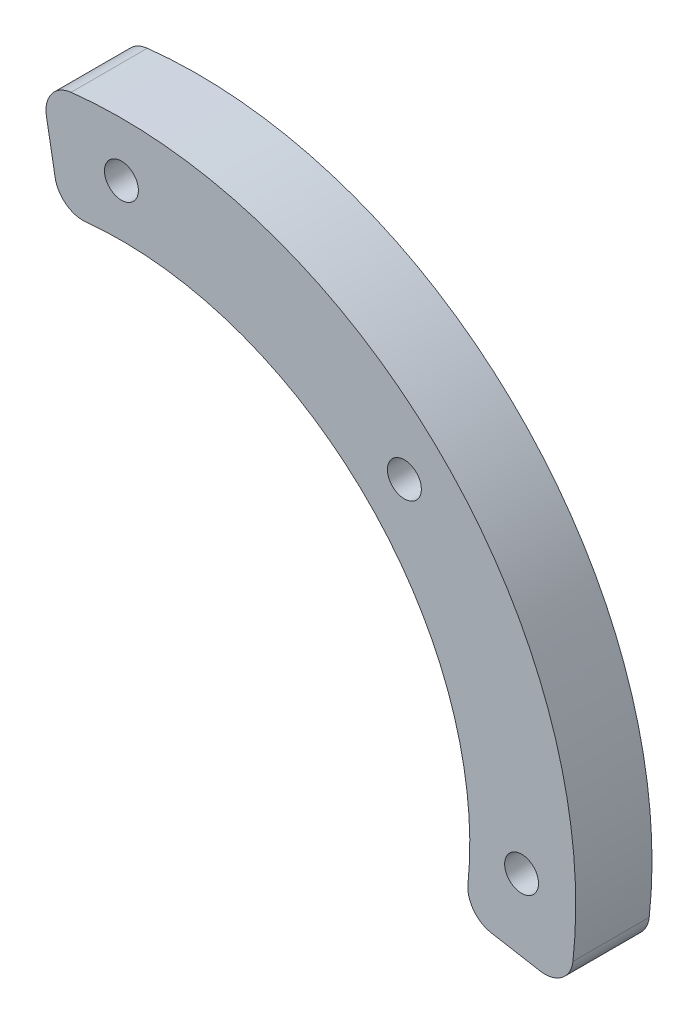
SolidWorks part; units mm, degrees
ref_plane "前视基准面" through (0, 0, 0) normal (0, 0, 1) x (1, 0, 0)
ref_plane "上视基准面" through (0, 0, 0) normal (0, 1, 0) x (1, 0, 0)
ref_plane "右视基准面" through (0, 0, 0) normal (1, 0, 0) x (0, 0, -1)
other "Configuration Table"
sketch "草图1" plane through (0, 0, 0) normal (0, 0, 1) x (1, 0, 0)
  line L0 (-28.0853, 24.4553) -> (-27.1565, 19.2748)
  line L1 (19.1535, -27.0342) -> (24.336, -27.9445)
  circle A0 centre (22.3824, -19.9865) radius 1.8
  circle A1 centre (9.9344, 10.0655) radius 1.8
  circle A2 centre (-20.1176, 22.5135) radius 1.8
  arc A3 (-27.1565, 19.2748) -> (-23.8972, 16.8199) centre (-24.2036, 19.8042) ccw
  arc A4 (16.6882, -23.7725) -> (-23.8972, 16.8199) centre (-20.1176, -19.9865) ccw
  arc A5 (16.6882, -23.7725) -> (19.1535, -27.0342) centre (19.6725, -24.0794) ccw
  arc A6 (24.336, -27.9445) -> (27.8366, -25.3214) centre (24.855, -24.9897) ccw
  arc A7 (27.8366, -25.3214) -> (-25.4649, 27.9662) centre (-20.1176, -19.9865) ccw
  arc A8 (-25.4649, 27.9662) -> (-28.0853, 24.4553) centre (-25.1324, 24.9847) ccw
extrude "凸台-拉伸1" add sketch "草图1" along normal blind 8.1
